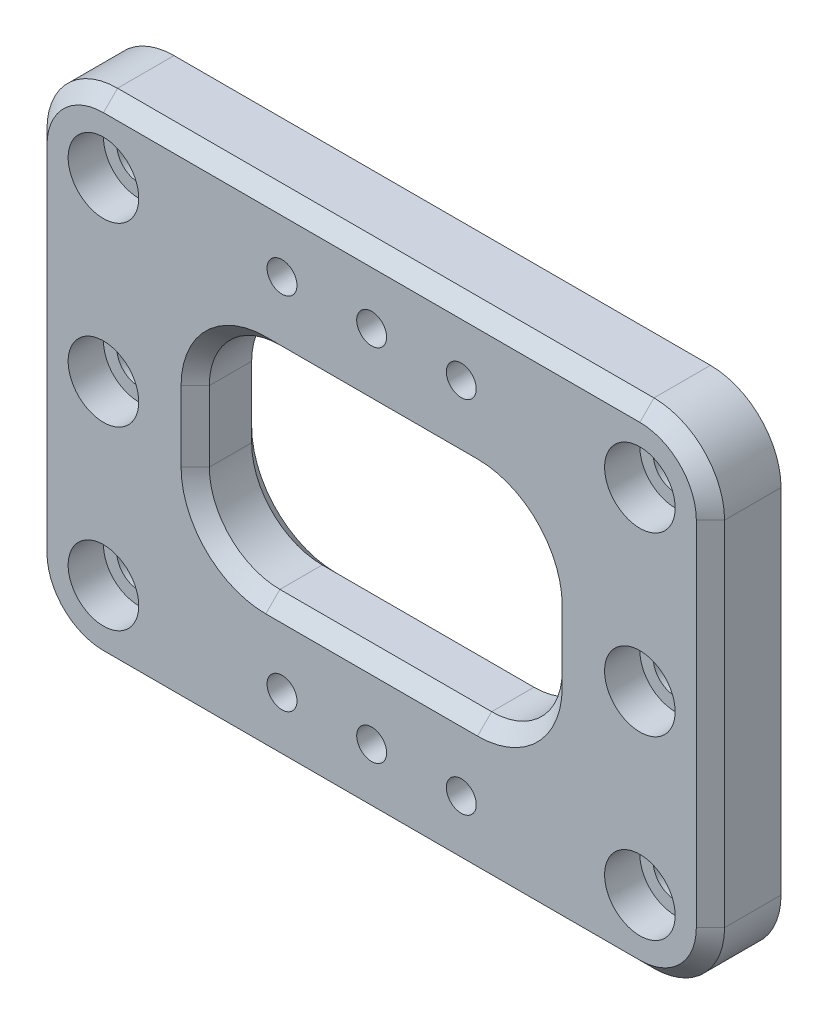
SolidWorks part; units mm, degrees
ref_plane "前视基准面" through (0, 0, 0) normal (0, 0, 1) x (1, 0, 0)
ref_plane "上视基准面" through (0, 0, 0) normal (0, 1, 0) x (1, 0, 0)
ref_plane "右视基准面" through (0, 0, 0) normal (1, 0, 0) x (0, 0, -1)
sketch "草图1" plane through (0, 0, 0) normal (0, 0, 1) x (1, 0, 0)
  line L1 (-48, 35) -> (48, 35)
  line L2 (-48, 35) -> (-48, -35)
  line L3 (-48, -35) -> (48, -35)
  line L4 (48, 35) -> (48, -35)
  line L5 (-48, 35) -> (48, -35) construction
  line L6 (-48, -35) -> (48, 35) construction
  point P0 (0, 0)
extrude "凸台-拉伸1" add sketch "草图1" along normal blind 10
fillet "圆角1" radius 10 4 edges at (48, -35, 5) (-48, -35, 5) (48, 35, 5) (-48, 35, 5)
sketch "草图2" plane through (0, 0, 10) normal (0, 0, 1) x (1, 0, 0)
  line L0 (0, 35) -> (0, 25.5) construction
  line L1 (38, 35) -> (-38, 35) construction
  line L2 (0, 25.5) -> (-12.7, 25.5) construction
  line L3 (0, 25.5) -> (0, -25.5) construction
  line L4 (0, -25.5) -> (-12.7, -25.5) construction
  line L5 (0, -25.5) -> (12.7, -25.5) construction
  circle A0 centre (0, 25.5) radius 2.12
  circle A1 centre (-12.7, 25.5) radius 2.12
  circle A2 centre (12.7, 25.5) radius 2.12
  circle A3 centre (-12.7, -25.5) radius 2.12
  circle A4 centre (0, -25.5) radius 2.12
  circle A5 centre (12.7, -25.5) radius 2.12
  point P16 (0, 0)
  dimension "D1" = 12.7
  dimension "D2" = 0
extrude "切除-拉伸1" cut sketch "草图2" against normal blind 10
sketch "草图3" plane through (0, 0, 10) normal (0, 0, 1) x (1, 0, 0)
  line L0 (-48, 0) -> (-38, 0) construction
  line L1 (-48, 25) -> (-48, -25) construction
  line L2 (-38, 0) -> (-38, 25) construction
  line L3 (-38, 0) -> (-38, -25) construction
  line L4 (0, 0) -> (0, 10) construction
  circle A0 centre (-38, 25) radius 5
  circle A1 centre (-38, 0) radius 5
  circle A2 centre (-38, -25) radius 5
  circle A3 centre (38, -25) radius 5
  circle A4 centre (38, 0) radius 5
  circle A5 centre (38, 25) radius 5
extrude "切除-拉伸2" cut sketch "草图3" against normal blind 5
sketch "草图4" plane through (0, 0, 5) normal (0, 0, 1) x (1, 0, 0)
  circle A0 centre (-38, 25) radius 3.1
  circle A1 centre (-38, 0) radius 3.1
  circle A2 centre (-38, -25) radius 3.1
  circle A3 centre (38, 25) radius 3.1
  circle A4 centre (38, 0) radius 3.1
  circle A5 centre (38, -25) radius 3.1
extrude "切除-拉伸3" cut sketch "草图4" against normal blind 5
chamfer "倒角1" distance 1 angle 45 6 edges at (41.1, 25, 0) (41.1, 0, 0) (41.1, -25, 0) (-34.9, -25, 0) (-34.9, 0, 0) (-34.9, 25, 0)
chamfer "倒角2" distance 2 angle 45 8 edges at (48, 0, 10) (45.0711, 32.0711, 10) (45.0711, -32.0711, 10) (0, 35, 10) (0, -35, 10) (-45.0711, 32.0711, 10) (-45.0711, -32.0711, 10) (-48, 0, 10)
sketch "草图5" plane through (0, 0, 10) normal (0, 0, 1) x (1, 0, 0)
  line L1 (-25, -15) -> (25, -15)
  line L2 (-25, -15) -> (-25, 15)
  line L3 (-25, 15) -> (25, 15)
  line L4 (25, -15) -> (25, 15)
  line L5 (-25, -15) -> (25, 15) construction
  line L6 (-25, 15) -> (25, -15) construction
  point P0 (0, 0)
extrude "切除-拉伸4" cut sketch "草图5" against normal blind 10
fillet "圆角2" radius 10 4 edges at (25, -15, 5) (25, 15, 5) (-25, -15, 5) (-25, 15, 5)
chamfer "倒角3" distance 2 angle 45 16 edges at (22.0711, -12.0711, 0) (22.0711, 12.0711, 0) (0, -15, 0) (0, 15, 0) (-22.0711, -12.0711, 0) (-22.0711, 12.0711, 0) (22.0711, -12.0711, 10) (0, -15, 10) (22.0711, 12.0711, 10) (-22.0711, -12.0711, 10) (0, 15, 10) (-22.0711, 12.0711, 10) (25, 0, 0) (-25, 0, 0) (25, 0, 10) (-25, 0, 10)
